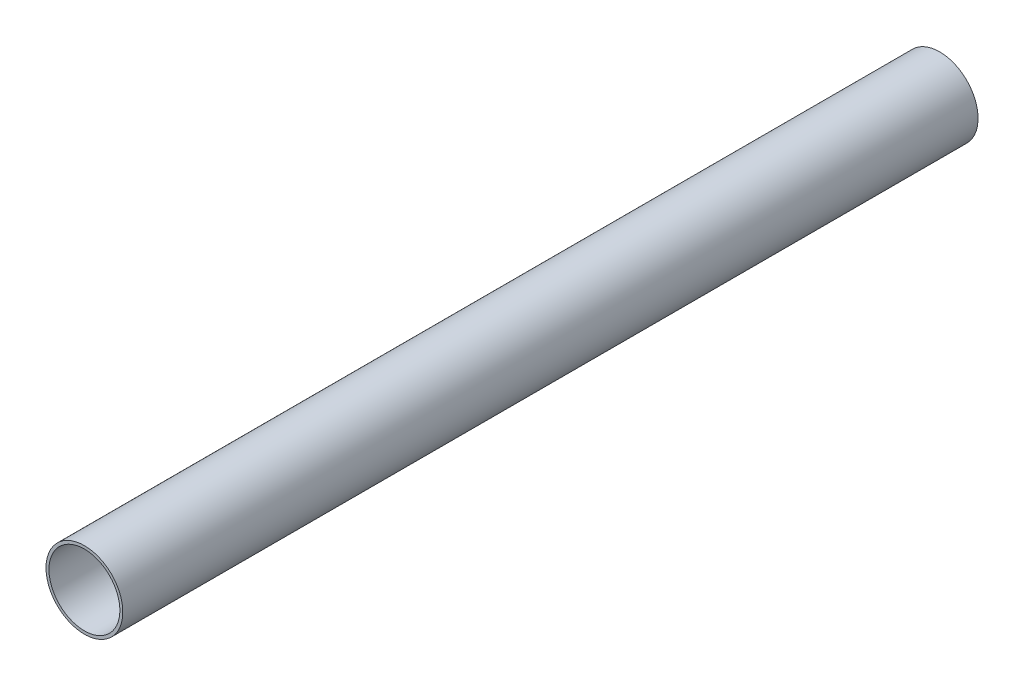
SolidWorks part; units mm, degrees
ref_plane "Front Plane" through (0, 0, 0) normal (0, 0, 1) x (1, 0, 0)
ref_plane "Top Plane" through (0, 0, 0) normal (0, 1, 0) x (1, 0, 0)
ref_plane "Right Plane" through (0, 0, 0) normal (1, 0, 0) x (0, 0, -1)
sketch "Cardboard Motor Tube Sketch" plane through (0, 0, 0) normal (0, 0, 1) x (1, 0, 0)
  circle A0 centre (0, 0) radius 20.6375
  circle A1 centre (0, 0) radius 19.05
  dimension "D1" = 41.275
  dimension "D2" = 38.1
extrude "Cardboard Motor Tube Extrude" add sketch "Cardboard Motor Tube Sketch" along normal blind 609.6
ref_plane "Cardboard Motor Tube Cut Plane" through (0, 0, 459.6) normal (0, 0, 1) x (1, 0, 0)
other "Cardboard Motor Tube Surface Cut"
